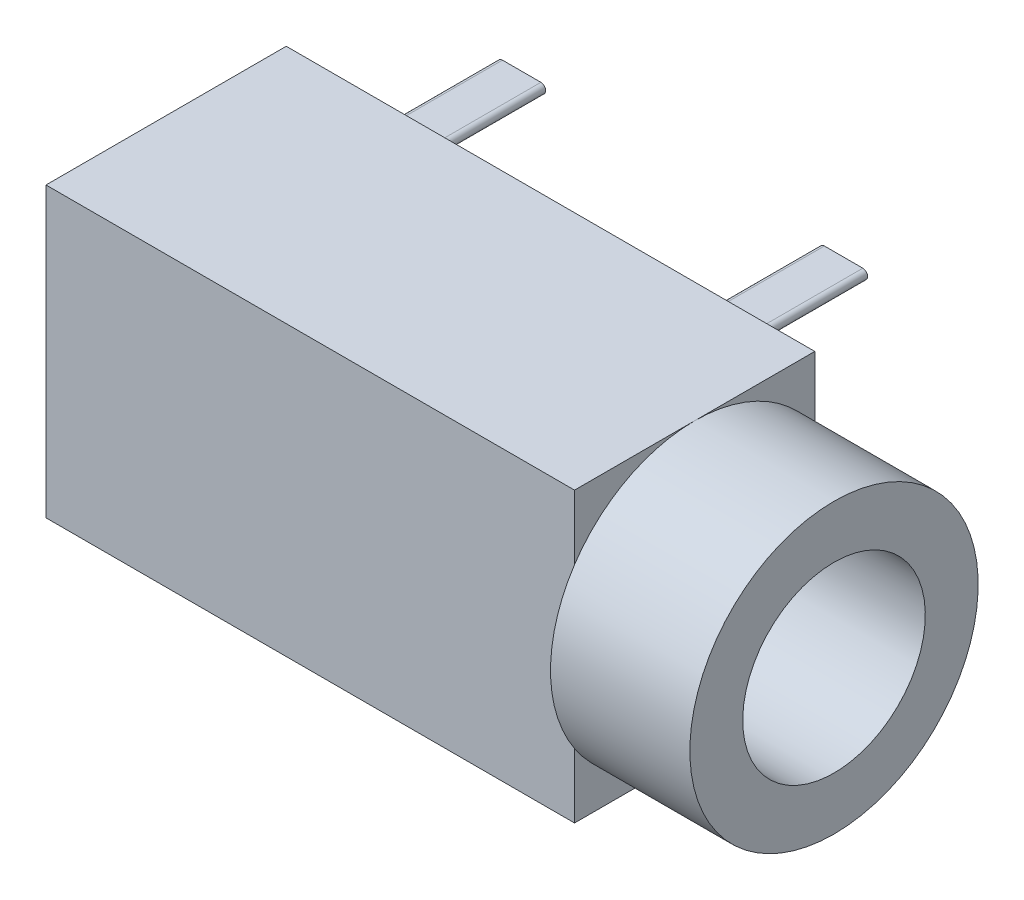
SolidWorks part; units mm, degrees
ref_plane "Front Plane" through (0, 0, 0) normal (0, 0, 1) x (1, 0, 0)
ref_plane "Top Plane" through (0, 0, 0) normal (0, 1, 0) x (1, 0, 0)
ref_plane "Right Plane" through (0, 0, 0) normal (1, 0, 0) x (0, 0, -1)
sketch "Sketch1" plane through (0, 0, 0) normal (0, 0, 1) x (1, 0, 0)
  line L1 (-5.5, 3) -> (5.5, 3)
  line L2 (-5.5, 3) -> (-5.5, -3)
  line L3 (-5.5, -3) -> (5.5, -3)
  line L4 (5.5, 3) -> (5.5, -3)
  line L5 (-5.5, 3) -> (5.5, -3) construction
  line L6 (-5.5, -3) -> (5.5, 3) construction
  point P0 (0, 0)
  dimension "D1" = 6
  dimension "D2" = 11
extrude "Boss-Extrude1" add sketch "Sketch1" along normal blind 5
sketch "Sketch2" plane through (5.5, 0, 0) normal (1, 0, 0) x (0, 0, -1)
  line L0 (0, 0) -> (-5, 0) construction
  line L1 (-5, -3) -> (-5, 3) construction
  circle A0 centre (-2.5, 0) radius 3
  circle A1 centre (-2.5, 0) radius 1.9
  dimension "D1" = 6
  dimension "D2" = 1.1
  dimension "D3" = 3.8
extrude "Boss-Extrude2" add sketch "Sketch2" along normal blind 2.9
sketch "Sketch3" plane through (0, 0, 0) normal (0, 0, -1) x (-1, 0, 0)
  line L0 (-3.6, 2) -> (-2.8, 2) construction
  line L1 (-3.6, 2.1) -> (-2.8, 2.1)
  line L2 (-3.6, 1.9) -> (-2.8, 1.9)
  line L3 (3.9, 2) -> (3.1, 2) construction
  line L4 (3.9, 1.9) -> (3.1, 1.9)
  line L5 (3.9, 2.1) -> (3.1, 2.1)
  line L6 (-1.7, -2) -> (-0.9, -2) construction
  line L7 (-1.7, -1.9) -> (-0.9, -1.9)
  line L8 (-1.7, -2.1) -> (-0.9, -2.1)
  line L9 (-5.5, 3) -> (-5.5, 1.6583) construction
  line L10 (5.5, 3) -> (5.5, -3) construction
  line L11 (-5.5, -1.6583) -> (-5.5, -3) construction
  line L12 (-5.5, 3) -> (5.5, 3) construction
  line L13 (5.5, -3) -> (-5.5, -3) construction
  arc A0 (-3.6, 2.1) -> (-3.6, 1.9) centre (-3.6, 2) ccw
  arc A1 (-2.8, 1.9) -> (-2.8, 2.1) centre (-2.8, 2) ccw
  arc A2 (3.9, 1.9) -> (3.9, 2.1) centre (3.9, 2) ccw
  arc A3 (3.1, 2.1) -> (3.1, 1.9) centre (3.1, 2) ccw
  arc A4 (-1.7, -1.9) -> (-1.7, -2.1) centre (-1.7, -2) ccw
  arc A5 (-0.9, -2.1) -> (-0.9, -1.9) centre (-0.9, -2) ccw
  point P2 (-3.2, 2)
  point P8 (3.5, 2)
  point P15 (-1.3, -2)
  point P31 (-3.2, 1.9)
  dimension "D1" = 2.3
  dimension "D2" = 2
  dimension "D3" = 4.2
  dimension "D4" = 1
  dimension "D5" = 1
  dimension "D6" = 0.8
  dimension "D7" = 0.2
  dimension "D8" = 0.2
  dimension "D9" = 0.2
extrude "Boss-Extrude3" add sketch "Sketch3" along normal blind 2.9
